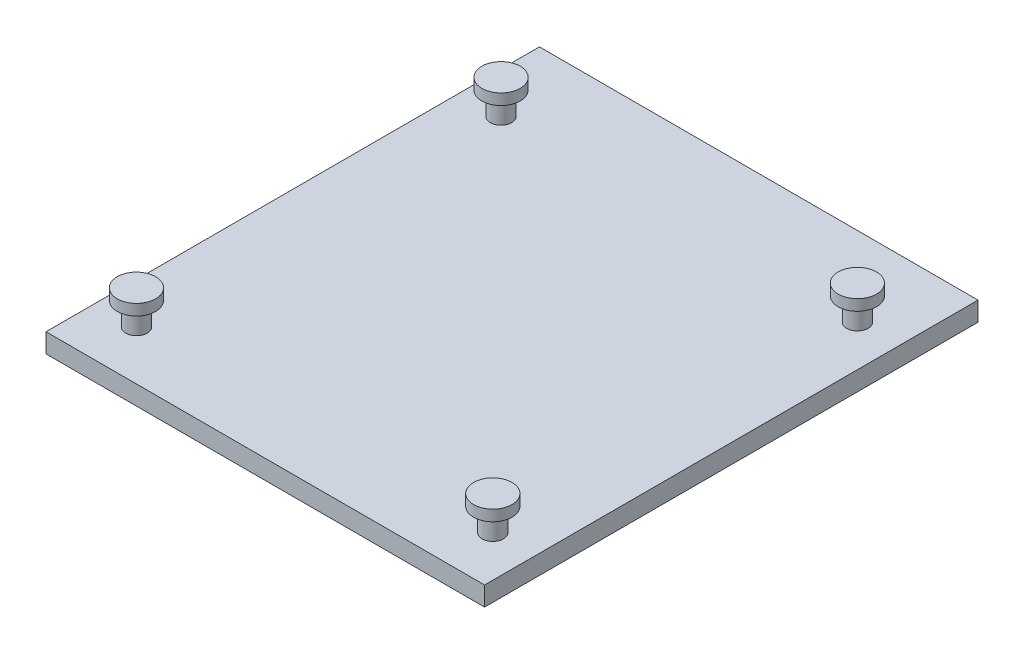
SolidWorks part; units mm, degrees
ref_plane "Front Plane" through (0, 0, 0) normal (0, 0, 1) x (1, 0, 0)
ref_plane "Top Plane" through (0, 0, 0) normal (0, 1, 0) x (1, 0, 0)
ref_plane "Right Plane" through (0, 0, 0) normal (1, 0, 0) x (0, 0, -1)
sketch "Sketch1" plane through (0, 0, 0) normal (0, 1, 0) x (1, 0, 0)
  line L1 (-40, -45) -> (40, -45)
  line L2 (-40, -45) -> (-40, 45)
  line L3 (-40, 45) -> (40, 45)
  line L4 (40, -45) -> (40, 45)
  line L5 (-40, -45) -> (40, 45) construction
  line L6 (-40, 45) -> (40, -45) construction
  point P0 (0, 0)
  dimension "D1" = 80
  dimension "D2" = 90
extrude "Boss-Extrude1" add sketch "Sketch1" against normal blind 3.5
sketch "Sketch2" plane through (0, 0, 0) normal (0, 1, 0) x (1, 0, 0)
  line L0 (-40, 45) -> (-40, -45) construction
  line L1 (40, 45) -> (-40, 45) construction
  line L2 (-40, -45) -> (40, -45) construction
  line L3 (40, -45) -> (40, 45) construction
  circle A0 centre (-32.5, 30.5) radius 1.95
  circle A1 centre (32.5, 30.5) radius 1.95
  circle A2 centre (32.5, -36) radius 1.95
  circle A3 centre (-32.5, -36) radius 1.95
  point P12 (0, 0)
  point P13 (0, 0)
  point P18 (0, 0)
  point P19 (0, 0)
  point P20 (0, 0)
  point P21 (0, 0)
  dimension "D3" = 3.9
  dimension "D4" = 3.9
  dimension "D5" = 3.9
  dimension "D6" = 3.9
  dimension "D1" = 7.5
  dimension "D2" = 14.5
  dimension "D7" = 9
  dimension "D8" = 7.5
extrude "Boss-Extrude2" add sketch "Sketch2" along normal blind 4.2
sketch "Sketch3" plane through (0, 4.2, 0) normal (0, 1, 0) x (1, 0, 0)
  circle A0 centre (-32.5, 30.5) radius 3.5
  circle A1 centre (32.5, 30.5) radius 3.5
  circle A2 centre (-32.5, -36) radius 3.5
  circle A4 centre (32.5, -36) radius 3.5
  dimension "D1" = 7
  dimension "D2" = 7
  dimension "D3" = 7
  dimension "D4" = 7
extrude "Boss-Extrude3" add sketch "Sketch3" along normal blind 2
